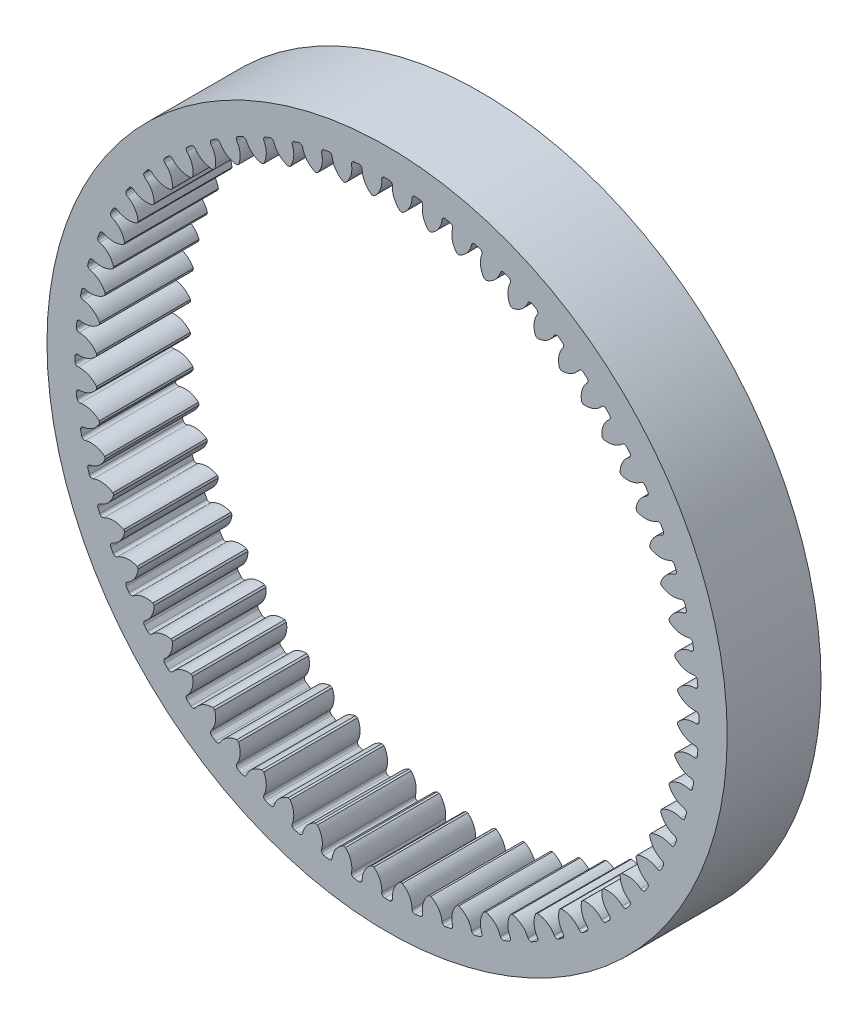
SolidWorks part; units mm, degrees
ref_plane "Front Plane" through (0, 0, 0) normal (0, 0, 1) x (1, 0, 0)
ref_plane "Top Plane" through (0, 0, 0) normal (0, 1, 0) x (1, 0, 0)
ref_plane "Right Plane" through (0, 0, 0) normal (1, 0, 0) x (0, 0, -1)
sketch "Sketch1" plane through (0, 0, 0) normal (0, 0, 1) x (1, 0, 0)
  circle A0 centre (0, 0) radius 62
  circle A1 centre (0, 0) radius 72.5
  dimension "D1" = 124
  dimension "D2" = 145
extrude "Ring Profile" add sketch "Sketch1" along normal mid plane 20
sketch "Sketch2" plane through (0, 0, 10) normal (0, 0, 1) x (1, 0, 0)
  line L0 (-0.519, 66.5) -> (0.519, 66.5)
  arc A1 (1.1419, 65.8236) -> (2.8208, 61.9358) centre (5.6267, 65.4538) ccw
  circle A2 centre (0, 0) radius 62 construction
  arc A3 (-0.519, 66.5) -> (-1.1419, 65.8236) centre (-0.519, 65.875) ccw
  arc A4 (-1.1419, 65.8236) -> (-2.8208, 61.9358) centre (-5.6267, 65.4538) cw
  circle A5 centre (0, 0) radius 62
  arc A6 (2.8208, 61.9358) -> (-2.8208, 61.9358) centre (0, 0) ccw
  arc A7 (0.519, 66.5) -> (1.1419, 65.8236) centre (0.519, 65.875) cw
  point P17 (0, 66.5)
  point P19 (1.25, 66.5)
  dimension "D3" = 4.5
  dimension "D6" = 0.625
  dimension "D2" = 1.25
  dimension "D4" = 1.5708
  dimension "D5" = 0
extrude "Teeth Profile" cut sketch "Sketch2" against normal through all
pattern_circular "Teeth Circular Pattern" count 64 over 360 about axis through (0, 0, 0) along (0, 0, 1) of "Teeth Profile"
